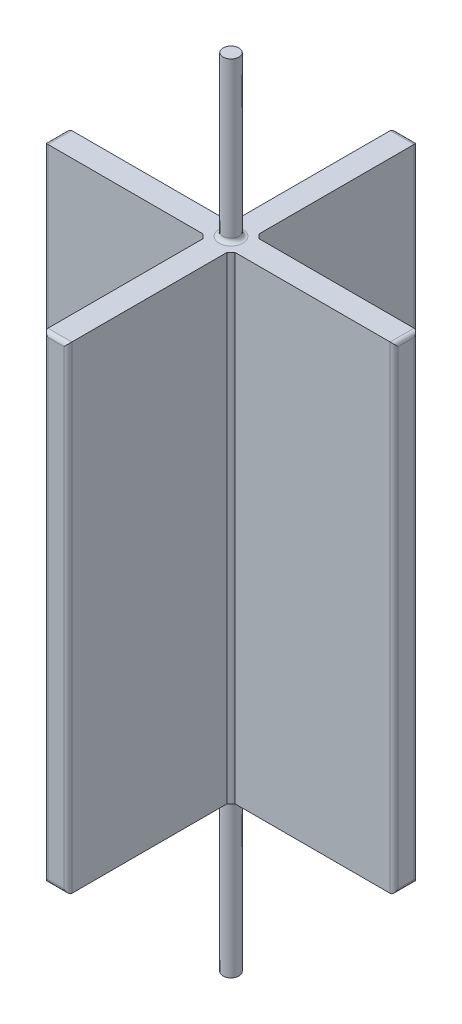
SolidWorks part; units mm, degrees
ref_plane "Front Plane" through (0, 0, 0) normal (0, 0, 1) x (1, 0, 0)
ref_plane "Top Plane" through (0, 0, 0) normal (0, 1, 0) x (1, 0, 0)
ref_plane "Right Plane" through (0, 0, 0) normal (1, 0, 0) x (0, 0, -1)
sketch "Sketch2" plane through (0, 0, 0) normal (0, 1, 0) x (1, 0, 0)
  line L0 (0, 6.4945) -> (0, -6.6178) construction
  line L1 (-6.913, 0) -> (8.4022, 0) construction
  line L2 (22, 1.5) -> (22, -1.5)
  line L3 (-1.5, 22) -> (1.5, 22)
  line L4 (1.5, 22) -> (1.5, 2)
  line L5 (-1.5, 22) -> (-1.5, 2)
  line L6 (22, -1.5) -> (2, -1.5)
  line L7 (22, 1.5) -> (2, 1.5)
  line L8 (1.5, -22) -> (-1.5, -22)
  line L9 (-1.5, -22) -> (-1.5, -2)
  line L10 (1.5, -22) -> (1.5, -2)
  line L11 (-22, -1.5) -> (-22, 1.5)
  line L12 (-22, 1.5) -> (-2, 1.5)
  line L13 (-22, -1.5) -> (-2, -1.5)
  circle A0 centre (0, 0) radius 2.5
  point P26 (0, -0.2913)
  point P27 (0, 0)
  dimension "D1" = 20
  dimension "D5" = 5
  dimension "D2" = 3
extrude "Boss-Extrude1" add sketch "Sketch2" along normal blind 60
fillet "Fillet1" radius 0.5 16 edges at (22, 30, 1.5) (22, 60, 0) (22, 30, -1.5) (22, 0, 0) (-1.5, 30, 22) (0, 60, 22) (1.5, 30, 22) (0, 0, 22) (-22, 30, -1.5) (-22, 60, 0) (-22, 30, 1.5) (-22, 0, 0) (1.5, 30, -22) (0, 60, -22) (-1.5, 30, -22) (0, 0, -22)
sketch "Sketch3" plane through (0, 0, 0) normal (0, 1, 0) x (1, 0, 0)
  circle A0 centre (0, 0) radius 1.0008
extrude "Cut-Extrude1" cut sketch "Sketch3" along normal up to surface (60 mm away) up to face at (0, 60, 0)
ref_plane "Plane1" through (0, 30, 0) normal (0, 1, 0) x (1, 0, 0)
sketch "Sketch4" plane through (0, 30, 0) normal (0, 1, 0) x (1, 0, 0)
  circle A0 centre (0, 0) radius 1.0008
extrude "Boss-Extrude2" add sketch "Sketch4" along normal mid plane 100
fillet "Fillet2" radius 0.5 2 edges at (0, 60, 1.0008) (0, 0, 1.0008)
